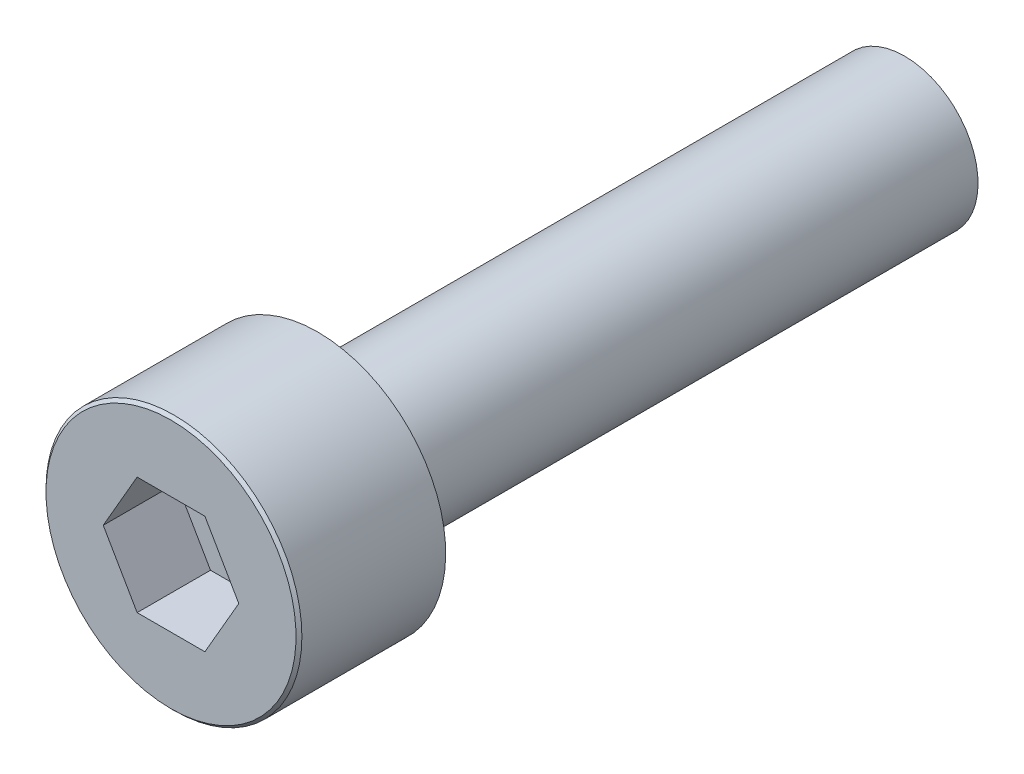
SolidWorks part; units mm, degrees
material "普通碳钢"
ref_plane "前视基准面" through (0, 0, 0) normal (0, 0, 1) x (1, 0, 0)
ref_plane "上视基准面" through (0, 0, 0) normal (0, 1, 0) x (1, 0, 0)
ref_plane "右视基准面" through (0, 0, 0) normal (1, 0, 0) x (0, 0, -1)
sketch "草图1" plane through (0, 0, 0) normal (1, 0, 0) x (0, 0, -1)
  line L0 (0, 0) -> (0, 4.36)
  line L1 (0, 4.36) -> (5, 4.36)
  line L2 (5, 4.36) -> (5, 2.5)
  line L3 (5, 2.5) -> (25, 2.5)
  line L4 (25, 2.5) -> (25, 0)
  line L5 (25, 0) -> (0, 0) construction
  line L6 (0, 0) -> (25, 0)
  dimension "D1" = 8.72
  dimension "D2" = 5
  dimension "D3" = 5
  dimension "D4" = 20
revolve "旋转1" add sketch "草图1" angle 360 about L5
cosmetic thread "装饰螺纹线1" parameters "D2"=4
sketch "草图2" plane through (0, 0, 0) normal (0, 0, 1) x (1, 0, 0)
  line L1 (1.1547, 2) -> (-1.1547, 2)
  line L2 (-1.1547, 2) -> (-2.3094, 0)
  line L3 (-2.3094, 0) -> (-1.1547, -2)
  line L4 (-1.1547, -2) -> (1.1547, -2)
  line L5 (1.1547, -2) -> (2.3094, 0)
  line L6 (2.3094, 0) -> (1.1547, 2)
  circle A0 centre (0, 0) radius 2 construction
  dimension "D1" = 4
extrude "切除-拉伸1" cut sketch "草图2" against normal blind 2.5
chamfer "装饰倒角" distance 0.1 angle 45 1 edges at (0, 4.36, 0)
